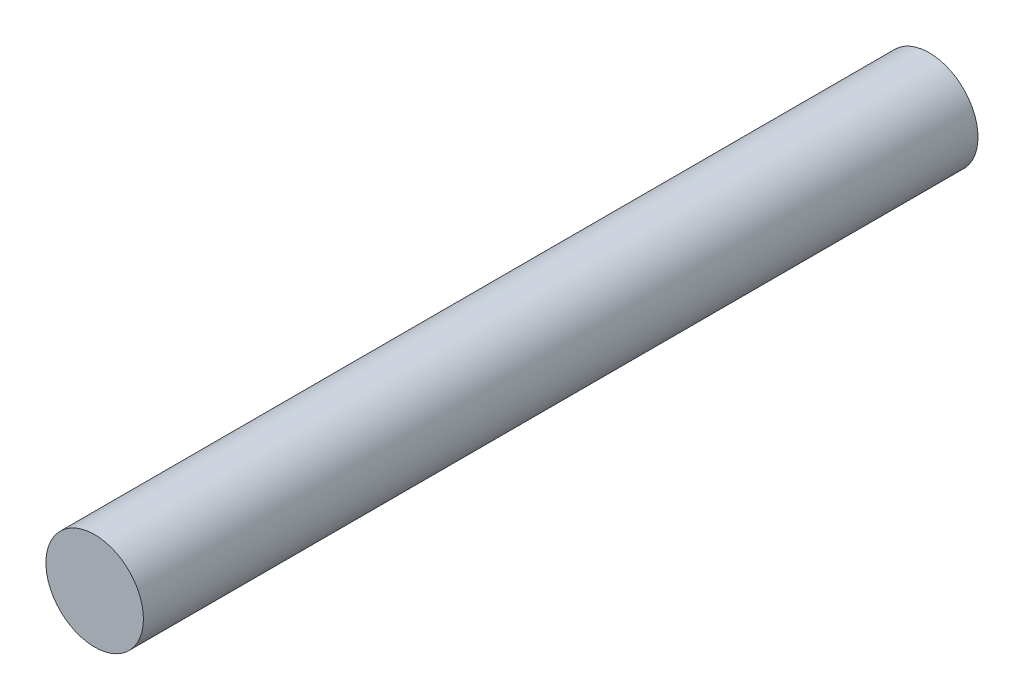
SolidWorks part; units mm, degrees
ref_plane "Front Plane" through (0, 0, 0) normal (0, 0, 1) x (1, 0, 0)
ref_plane "Top Plane" through (0, 0, 0) normal (0, 1, 0) x (1, 0, 0)
ref_plane "Right Plane" through (0, 0, 0) normal (1, 0, 0) x (0, 0, -1)
sketch "Sketch1" plane through (0, 0, 0) normal (0, 0, 1) x (1, 0, 0)
  circle A0 centre (0, 0) radius 1.25
  dimension "D1" = 2.5
extrude "Boss-Extrude1" add sketch "Sketch1" along normal blind 21.4
